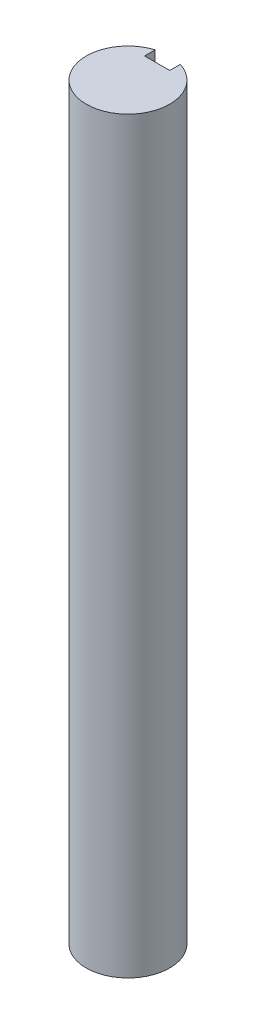
SolidWorks part; units mm, degrees
material "AISI 316 Annealed Stainless Steel Bar (SS)"
ref_plane "Front Plane" through (0, 0, 0) normal (0, 0, 1) x (1, 0, 0)
ref_plane "Top Plane" through (0, 0, 0) normal (0, 1, 0) x (1, 0, 0)
ref_plane "Right Plane" through (0, 0, 0) normal (1, 0, 0) x (0, 0, -1)
sketch "Sketch1" plane through (0, 0, 0) normal (0, 1, 0) x (1, 0, 0)
  line L0 (0, 0) -> (0, 50000) construction
  line L1 (0.3667, 0) -> (50000.3667, 0) construction
  line L2 (-1.1938, 3.7849) -> (-1.1938, 2.7781)
  line L3 (-1.1938, 2.7781) -> (0, 2.7781)
  line L4 (0, 3.9688) -> (50000, 3.9688) construction
  line L5 (1.1938, 2.7781) -> (0, 2.7781)
  line L6 (1.1938, 3.7849) -> (1.1938, 2.7781)
  arc A0 (-1.1938, 3.7849) -> (1.1938, 3.7849) centre (0, 0) ccw
  dimension "D1" = 7.9375
  dimension "D2" = 2.3876
  dimension "D3" = 1.1906
extrude "Boss-Extrude1" add sketch "Sketch1" along normal mid plane 71.12
ref_plane "keyPlane" through (0, 0, 0) normal (-1, 0, 0) x (0, 0, 1)
